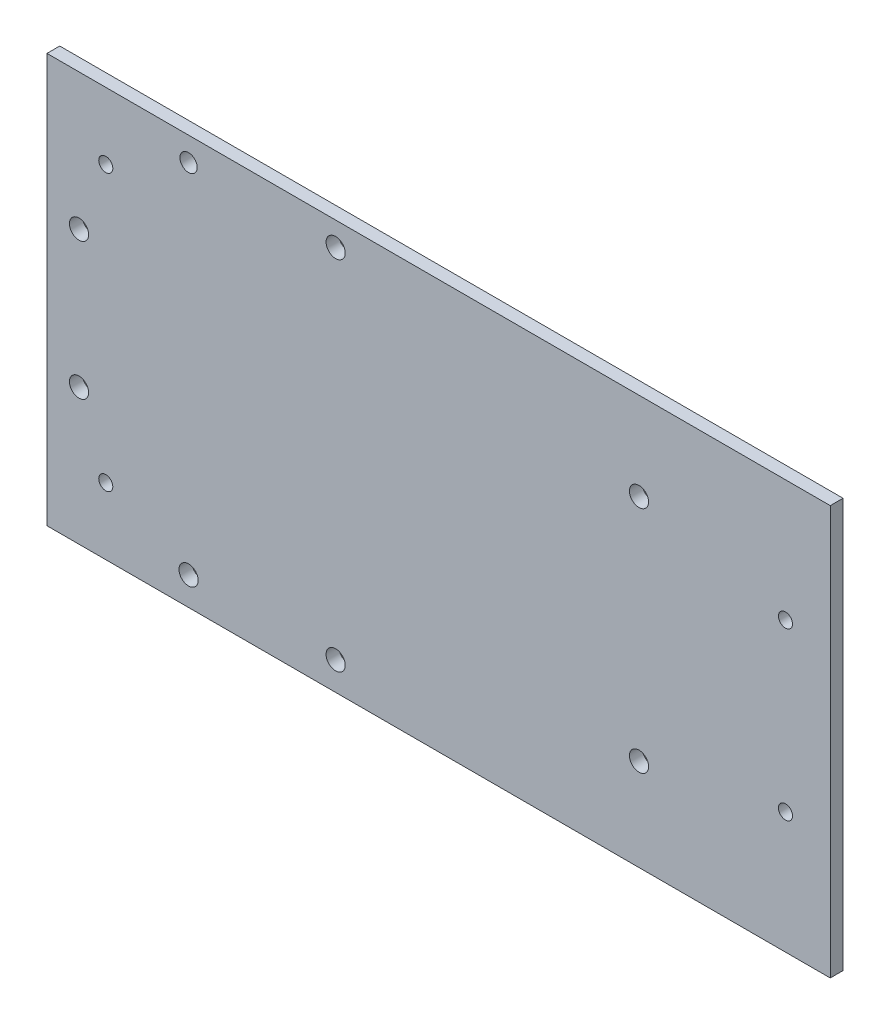
SolidWorks part; units mm, degrees
ref_plane "Front Plane" through (0, 0, 0) normal (0, 0, 1) x (1, 0, 0)
ref_plane "Top Plane" through (0, 0, 0) normal (0, 1, 0) x (1, 0, 0)
ref_plane "Right Plane" through (0, 0, 0) normal (1, 0, 0) x (0, 0, -1)
sketch "Sketch3" plane through (0, 0, 0) normal (0, 0, 1) x (1, 0, 0)
  line L1 (-153.175, 133.1957) -> (153.175, 133.1957)
  line L2 (-153.175, 133.1957) -> (-153.175, -26.8043)
  line L3 (-153.175, -26.8043) -> (153.175, -26.8043)
  line L4 (153.175, 133.1957) -> (153.175, -26.8043)
  line L5 (0, -26.8043) -> (0, 133.1957) construction
  line L6 (-153.175, 53.1957) -> (153.175, 53.1957) construction
  point P0 (0, 53.1957)
  dimension "D1" = 306.35
  dimension "D2" = 160
extrude "Boss-Extrude1" add sketch "Sketch3" along normal blind 5
sketch "Sketch4" plane through (0, 0, 0) normal (0, 0, -1) x (-1, 0, 0)
  line L0 (153.175, -26.8043) -> (-153.175, -26.8043) construction
  line L1 (153.175, 133.1957) -> (153.175, -26.8043) construction
  line L2 (-153.175, 133.1957) -> (153.175, 133.1957) construction
  line L3 (-153.175, -26.8043) -> (-153.175, 133.1957) construction
  circle A0 centre (140.6297, 26.4445) radius 3.75
  circle A1 centre (140.6297, 79.9469) radius 3.75
  circle A2 centre (97.795, -15.7543) radius 3.75
  circle A3 centre (40.265, -15.7543) radius 3.75
  circle A4 centre (97.795, 123.8957) radius 3.3724
  circle A5 centre (40.265, 123.8957) radius 3.75
  circle A6 centre (-78.375, 9.2457) radius 3.75
  circle A7 centre (-78.375, 98.8957) radius 3.75
  dimension "D3" = 7.5
  dimension "D4" = 7.5
  dimension "D7" = 11.05
  dimension "D9" = 57.53
  dimension "D12" = 25
  dimension "D13" = 25
  dimension "D1" = 53.2488
  dimension "D2" = 12.5453
  dimension "D5" = 12.5453
  dimension "D6" = 53.2488
  dimension "D8" = 55.38
  dimension "D10" = 139.65
  dimension "D11" = 9.3
  dimension "D14" = 74.8
  dimension "D15" = 74.8
  dimension "D16" = 57.53
extrude "Cut-Extrude1" cut sketch "Sketch4" against normal through all
sketch "Sketch5" plane through (0, 0, 0) normal (0, 0, -1) x (-1, 0, 0)
  line L0 (153.175, -26.8043) -> (-153.175, -26.8043) construction
  line L1 (-153.175, -26.8043) -> (-153.175, 133.1957) construction
  line L2 (-153.175, 133.1957) -> (153.175, 133.1957) construction
  line L3 (153.175, 133.1957) -> (153.175, -26.8043) construction
  circle A0 centre (-135.665, 20.6957) radius 2.75
  circle A1 centre (-135.665, 85.6957) radius 2.75
  circle A2 centre (130.175, 107.0957) radius 2.75
  circle A3 centre (130.175, -0.7043) radius 2.75
  point P12 (132.4661, 105.781)
  point P17 (130.175, -6.9282)
  dimension "D1" = 47.5
  dimension "D5" = 5.5
  dimension "D10" = 5.5
  dimension "D2" = 17.51
  dimension "D3" = 47.5
  dimension "D4" = 17.51
  dimension "D6" = 26.1
  dimension "D7" = 23
  dimension "D8" = 23
  dimension "D9" = 26.1
extrude "Cut-Extrude2" cut sketch "Sketch5" against normal through all
